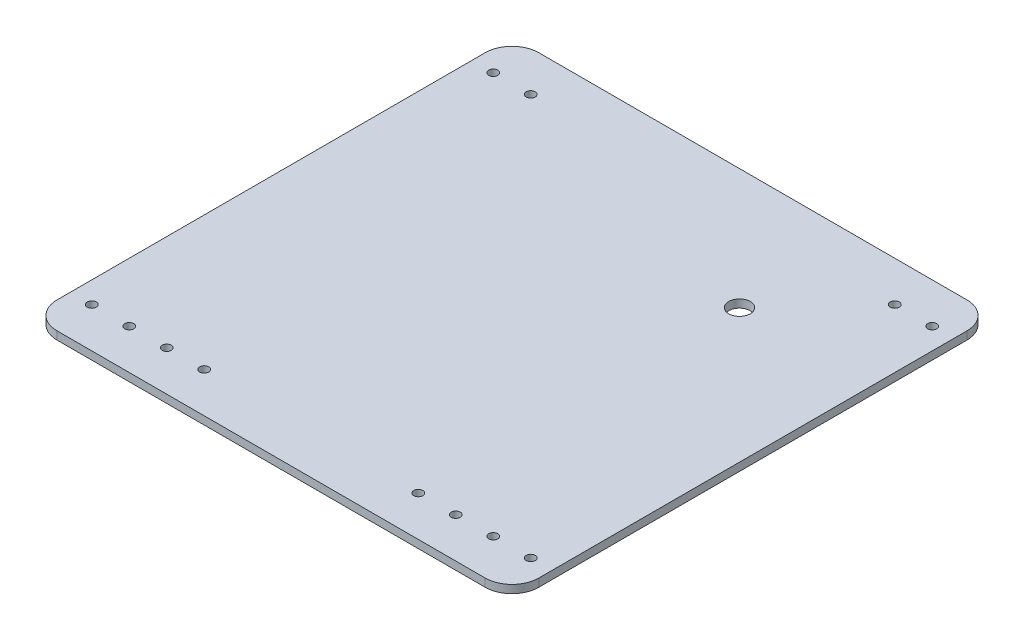
SolidWorks part; units mm, degrees
ref_plane "Front Plane" through (0, 0, 0) normal (0, 0, 1) x (1, 0, 0)
ref_plane "Top Plane" through (0, 0, 0) normal (0, 1, 0) x (1, 0, 0)
ref_plane "Right Plane" through (0, 0, 0) normal (1, 0, 0) x (0, 0, -1)
sketch "Sketch1" plane through (0, 0, 0) normal (0, 1, 0) x (1, 0, 0)
  line L1 (-90, 90) -> (90, 90)
  line L2 (-90, 90) -> (-90, -90)
  line L3 (-90, -90) -> (90, -90)
  line L4 (90, 90) -> (90, -90)
  line L5 (-90, 90) -> (90, -90) construction
  line L6 (-90, -90) -> (90, 90) construction
  point P0 (0, 0)
  dimension "D1" = 180
  dimension "D2" = 180
extrude "Boss-Extrude1" add sketch "Sketch1" along normal blind 3
fillet "Fillet1" radius 10 4 edges at (-90, 1.5, -90) (-90, 1.5, 90) (90, 1.5, -90) (90, 1.5, 90)
sketch "Sketch2" plane through (0, 3, 0) normal (0, 1, 0) x (1, 0, 0)
  circle A0 centre (-82, 75) radius 1.7
  circle A1 centre (-68, 75) radius 1.7
  circle A2 centre (68, 75) radius 1.7
  circle A3 centre (82, 75) radius 1.7
  circle A4 centre (-82, -75) radius 1.7
  circle A5 centre (-68, -75) radius 1.7
  circle A6 centre (68, -75) radius 1.7
  circle A7 centre (82, -75) radius 1.7
  circle A32 centre (-54, -75) radius 1.7
  circle A33 centre (54, -75) radius 1.7
  circle A34 centre (-40, -75) radius 1.7
  circle A35 centre (40, -75) radius 1.7
  dimension "D1" = 3.4
  dimension "D11" = 14
  dimension "D18" = 14
  dimension "D19" = 14
  dimension "D20" = 14
  dimension "D2" = 14
  dimension "D3" = 14
  dimension "D4" = 82
  dimension "D5" = 82
  dimension "D6" = 75
  dimension "D7" = 75
extrude "Cut-Extrude1" cut sketch "Sketch2" against normal up to surface (3 mm away) up to face at (0, 0, 0)
sketch "Sketch3" plane through (0, 3, 0) normal (0, 1, 0) x (1, 0, 0)
  circle A0 centre (40, 45) radius 4
extrude "Cut-Extrude2" cut sketch "Sketch3" against normal through all
